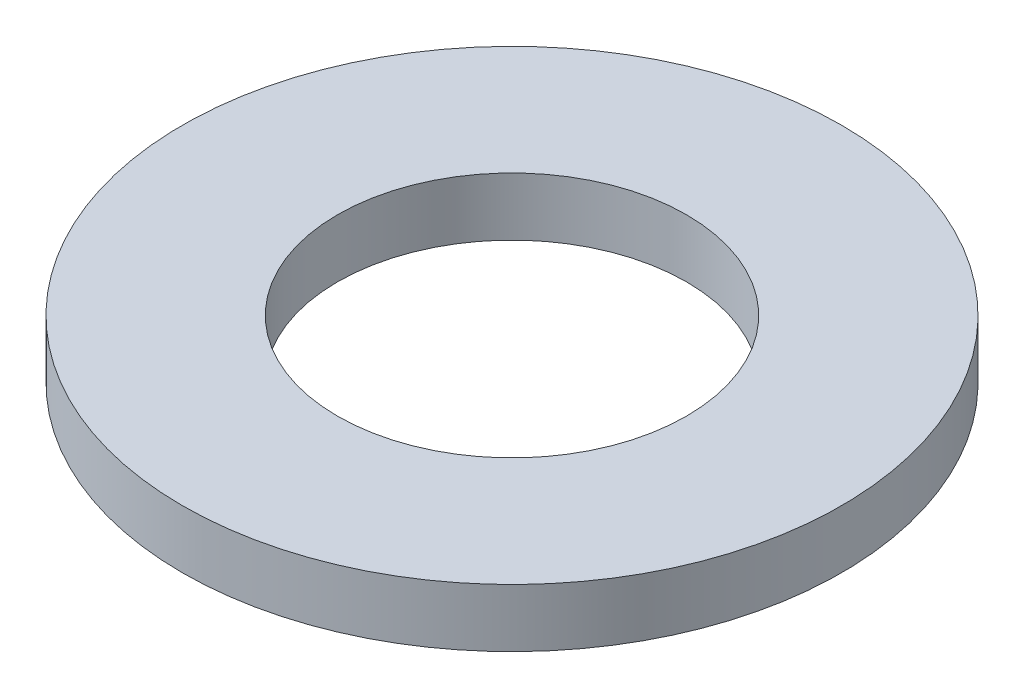
SolidWorks part; units mm, degrees
ref_plane "Front Plane" through (0, 0, 0) normal (0, 0, 1) x (1, 0, 0)
ref_plane "Top Plane" through (0, 0, 0) normal (0, 1, 0) x (1, 0, 0)
ref_plane "Right Plane" through (0, 0, 0) normal (1, 0, 0) x (0, 0, -1)
sketch "Sketch1" plane through (0, 0, 0) normal (0, 1, 0) x (1, 0, 0)
  circle A0 centre (0, 0) radius 4.5
  circle A1 centre (0, 0) radius 8.5
  dimension "D1" = 9
  dimension "D2" = 4
extrude "Boss-Extrude1" add sketch "Sketch1" along normal blind 1.5
